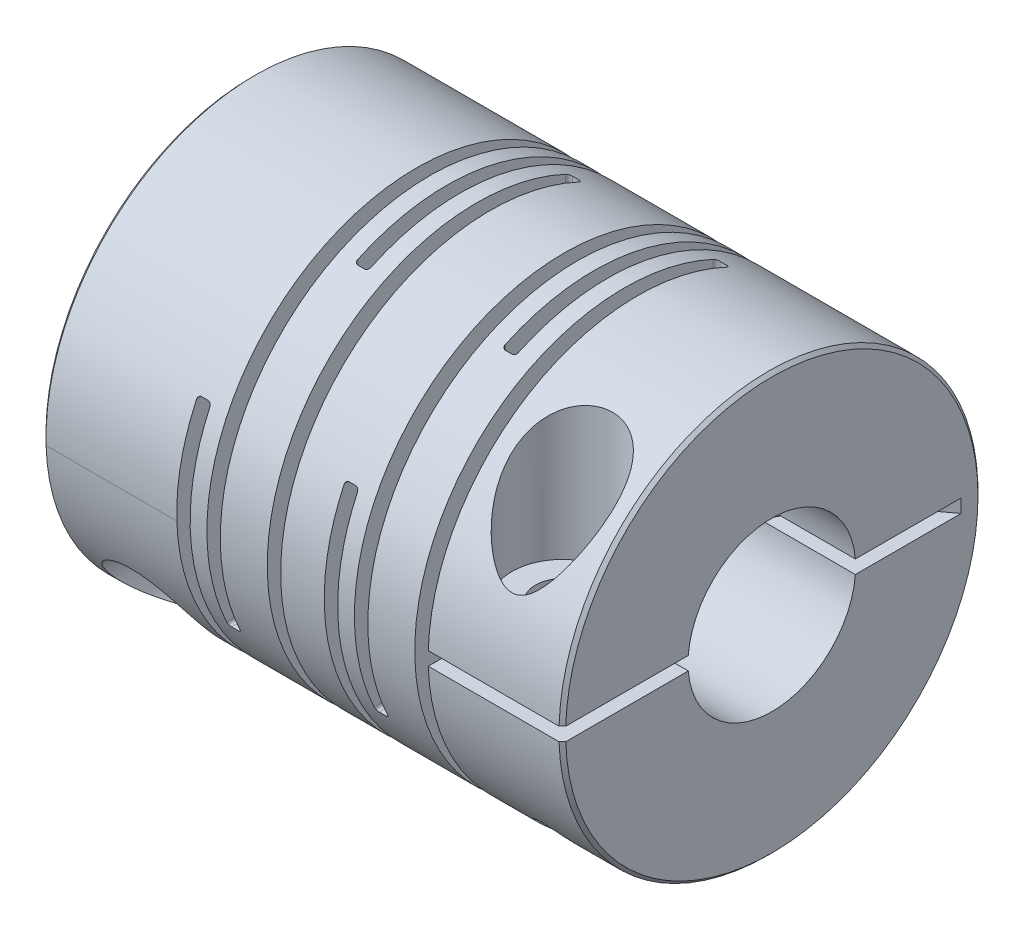
SolidWorks part; units mm, degrees
ref_plane "Front Plane" through (0, 0, 0) normal (0, 0, 1) x (1, 0, 0)
ref_plane "Top Plane" through (0, 0, 0) normal (0, 1, 0) x (1, 0, 0)
ref_plane "Right Plane" through (0, 0, 0) normal (1, 0, 0) x (0, 0, -1)
ref_plane "Plane1" through (0, 0, 12.5) normal (0, 0, 1) x (1, 0, 0)
ref_plane "Plane2" through (0, 12.5, 0) normal (0, 1, 0) x (1, 0, 0)
ref_plane "Plane3" through (31, 0, 0) normal (1, 0, 0) x (0, 0, -1)
sketch "Sketch1" plane through (0, 0, 0) normal (0, 0, 1) x (1, 0, 0)
  line L0 (0, 0) -> (31, 0) construction
  line L1 (0, 0) -> (31, 0)
  line L3 (0, 0) -> (0, 12.5)
  line L4 (0, 12.5) -> (31, 12.5)
  line L5 (31, 0) -> (31, 12.5)
  dimension "L" = 31
  dimension "D" = 25
revolve "Revolve1" add sketch "Sketch1" about L0
sketch "Sketch2" plane through (0, 0, 12.5) normal (0, 0, 1) x (1, 0, 0)
  line L0 (19.4, 12.5) -> (19.4, -5.3)
  line L1 (18.6, -5.3) -> (18.6, 12.5)
  line L2 (18.8, -5.5) -> (19.2, -5.5)
  line L3 (17.6, 5.3) -> (17.6, -12.5)
  line L4 (17.4, 5.5) -> (17, 5.5)
  line L5 (16.8, -12.5) -> (16.8, 5.3)
  line L6 (10.6, 12.5) -> (10.6, -5.3)
  line L7 (10, -5.5) -> (10.4, -5.5)
  line L8 (9.8, -5.3) -> (9.8, 12.5)
  line L9 (8.8, 5.3) -> (8.8, -12.5)
  line L10 (8.6, 5.5) -> (8.2, 5.5)
  line L11 (8, -12.5) -> (8, 5.3)
  line L12 (9.8, 12.5) -> (10.6, 12.5)
  line L13 (8, -12.5) -> (8.8, -12.5)
  line L14 (16.8, -12.5) -> (17.6, -12.5)
  line L15 (18.6, 12.5) -> (19.4, 12.5)
  line L16 (0, 0) -> (31, 0) construction
  line L17 (31, -8.8) -> (31, 8.8) construction
  arc A0 (19.2, -5.5) -> (19.4, -5.3) centre (19.2, -5.3) ccw
  arc A1 (18.6, -5.3) -> (18.8, -5.5) centre (18.8, -5.3) ccw
  arc A2 (17.6, 5.3) -> (17.4, 5.5) centre (17.4, 5.3) ccw
  arc A3 (17, 5.5) -> (16.8, 5.3) centre (17, 5.3) ccw
  arc A4 (10.4, -5.5) -> (10.6, -5.3) centre (10.4, -5.3) ccw
  arc A5 (9.8, -5.3) -> (10, -5.5) centre (10, -5.3) ccw
  arc A6 (8.8, 5.3) -> (8.6, 5.5) centre (8.6, 5.3) ccw
  arc A7 (8.2, 5.5) -> (8, 5.3) centre (8.2, 5.3) ccw
  dimension "FIX_3" = 0.2
  dimension "FIX_1" = 12.5
  dimension "D" = 25
  dimension "L_s" = 8
  dimension "MSM_1" = 5.3
  dimension "MSM_2" = 11.6
  dimension "MSM_4" = 0.8
extrude "Cut-Extrude1" cut sketch "Sketch2" against normal through all
sketch "Sketch3" plane through (0, 12.5, 0) normal (0, 1, 0) x (1, 0, 0)
  line L0 (21.2, 12.5) -> (21.2, -5.3)
  line L1 (20.4, -5.3) -> (20.4, 12.5)
  line L2 (20.6, -5.5) -> (21, -5.5)
  line L3 (23, 5.3) -> (23, -12.5)
  line L4 (22.8, 5.5) -> (22.4, 5.5)
  line L5 (22.2, -12.5) -> (22.2, 5.3)
  line L6 (12.4, 12.5) -> (12.4, -5.3)
  line L7 (11.8, -5.5) -> (12.2, -5.5)
  line L8 (11.6, -5.3) -> (11.6, 12.5)
  line L9 (14.2, 5.3) -> (14.2, -12.5)
  line L10 (14, 5.5) -> (13.6, 5.5)
  line L11 (13.4, -12.5) -> (13.4, 5.3)
  line L12 (11.6, 12.5) -> (12.4, 12.5)
  line L13 (13.4, -12.5) -> (14.2, -12.5)
  line L14 (22.2, -12.5) -> (23, -12.5)
  line L15 (20.4, 12.5) -> (21.2, 12.5)
  line L16 (0, 0) -> (31, 0) construction
  line L17 (31, -8.8) -> (31, 8.8) construction
  arc A0 (21, -5.5) -> (21.2, -5.3) centre (21, -5.3) ccw
  arc A1 (20.4, -5.3) -> (20.6, -5.5) centre (20.6, -5.3) ccw
  arc A2 (23, 5.3) -> (22.8, 5.5) centre (22.8, 5.3) ccw
  arc A3 (22.4, 5.5) -> (22.2, 5.3) centre (22.4, 5.3) ccw
  arc A4 (12.2, -5.5) -> (12.4, -5.3) centre (12.2, -5.3) ccw
  arc A5 (11.6, -5.3) -> (11.8, -5.5) centre (11.8, -5.3) ccw
  arc A6 (14.2, 5.3) -> (14, 5.5) centre (14, 5.3) ccw
  arc A7 (13.6, 5.5) -> (13.4, 5.3) centre (13.6, 5.3) ccw
  dimension "FIX_4" = 0.2
  dimension "FIX_1" = 12.5
  dimension "D" = 25
  dimension "L_s" = 8
  dimension "MSM_1" = 5.3
  dimension "MSM_2" = 11.6
  dimension "MSM_4" = 0.8
extrude "Cut-Extrude2" cut sketch "Sketch3" against normal through all
chamfer "Chamfer1" distance 0.2 2 edges at (31, 0, 12.5) (0, 0, 12.5)
sketch "Sketch4" plane through (0, 0, 0) normal (0, 0, 1) x (1, 0, 0)
  line L1 (0, 0) -> (25.1364, 0) construction
  line L2 (8.4, -12.5) -> (-11.6, -12.5)
  line L3 (-11.6, -12.5) -> (-11.6, 15)
  line L4 (8.4, -5) -> (8.4, -12.5)
  line L6 (-11.6, 15) -> (8.4, 15) construction
  line L7 (8.4, 15) -> (8.4, -12.5) construction
  arc A1 (8.4, -5) -> (-11.6, 15) centre (-11.6, -5) ccw
  dimension "FIX_1" = 12.5
  dimension "MSM_5" = 20
  dimension "MSM_6" = 8.4
  dimension "MSM_7" = 7.5
extrude "Cut-Extrude3" cut sketch "Sketch4" against normal mid plane 0.8
sketch "Sketch5" plane through (0, 0, 0) normal (0, 1, 0) x (1, 0, 0)
  line L0 (22.6, -12.5) -> (42.6, -12.5)
  line L1 (42.6, -12.5) -> (42.6, 15)
  line L2 (22.6, -5) -> (22.6, -12.5)
  line L3 (42.6, 15) -> (22.6, 15) construction
  line L4 (22.6, 15) -> (22.6, -12.5) construction
  line L5 (0, 0) -> (31, 0) construction
  line L6 (31, -8.8) -> (31, 8.8) construction
  arc A0 (42.6, 15) -> (22.6, -5) centre (42.6, -5) ccw
  dimension "FIX_1" = 12.5
  dimension "MSM_5" = 20
  dimension "MSM_6" = 8.4
  dimension "MSM_7" = 7.5
extrude "Cut-Extrude4" cut sketch "Sketch5" against normal mid plane 0.8
hole_wizard "Socket Head Cap Screw1" positions "Sketch8" profile "Sketch7" counterbore size "M2.5" standard "JIS"
sketch "Sketch8" plane through (0, 0, 12.5) normal (0, 0, 1) x (1, 0, 0)
  point P0 (4, -8.5)
  dimension "A" = 8.5
  dimension "F" = 4
sketch "Sketch7" plane through (4, -8.5, 12.5) normal (1, 0, 0) x (0, -1, 0)
  line L0 (0, 0) -> (0, 12.1)
  line L1 (0, 12.1) -> (1.6, 12.1)
  line L3 (1.6, 12.1) -> (1.6, 9.5)
  line L4 (1.6, 9.5) -> (3, 9.5)
  line L5 (3, 9.5) -> (3, 0)
  line L7 (3, 0) -> (0, 0)
  line L11 (0, 0) -> (0, 12.1) construction
  dimension "Thru Hole Depth" = 12.1
  dimension "MSM_8" = 6
  dimension "MSM_9" = 3.2
  dimension "MSM_10" = 9.5
hole_wizard "Tap1" positions "Sketch10" profile "Sketch9" hole size "M2x0.4" standard "JIS" end condition through all
sketch "Sketch10" plane through (0, 0, -0.4) normal (0, 0, 1) x (1, 0, 0)
  point P0 (4, -8.5)
  dimension "A" = 8.5
  dimension "F" = 4
sketch "Sketch9" plane through (4, -8.5, -0.4) normal (1, 0, 0) x (0, -1, 0)
  line L0 (0, 0) -> (0, 12.1)
  line L1 (0, 12.1) -> (1.2295, 12.1)
  line L2 (1.2295, 12.1) -> (1.2295, 0)
  line L5 (1.2295, 0) -> (0, 0)
  line L11 (0, 0) -> (0, 12.1) construction
  dimension "Thru Hole Depth" = 12.1
  dimension "STD" = 2.459
cosmetic thread "Thread1" parameters "M"=3
hole_wizard "Socket Head Cap Screw2" positions "Sketch12" profile "Sketch11" counterbore size "M2.5" standard "JIS"
sketch "Sketch12" plane through (0, 12.5, 0) normal (0, 1, 0) x (1, 0, 0)
  line L4 (31, -8.8) -> (31, 8.8) construction
  point P0 (27, -8.5)
  dimension "A" = 8.5
  dimension "F" = 4
sketch "Sketch11" plane through (27, 12.5, 8.5) normal (1, 0, 0) x (0, 0, 1)
  line L0 (0, 0) -> (0, 12.1)
  line L1 (0, 12.1) -> (1.6, 12.1)
  line L3 (1.6, 12.1) -> (1.6, 9.5)
  line L4 (1.6, 9.5) -> (3, 9.5)
  line L5 (3, 9.5) -> (3, 0)
  line L7 (3, 0) -> (0, 0)
  line L11 (0, 0) -> (0, 12.1) construction
  dimension "Thru Hole Depth" = 12.1
  dimension "MSM_8" = 6
  dimension "MSM_9" = 3.2
  dimension "MSM_10" = 9.5
hole_wizard "Tap2" positions "Sketch14" profile "Sketch13" hole size "M2x0.4" standard "JIS" end condition through all
sketch "Sketch14" plane through (0, -0.4, 0) normal (0, 1, 0) x (1, 0, 0)
  line L0 (31, -8.8) -> (31, 8.8) construction
  point P0 (27, -8.5)
  dimension "A" = 8.5
  dimension "F" = 4
sketch "Sketch13" plane through (27, -0.4, 8.5) normal (1, 0, 0) x (0, 0, 1)
  line L0 (0, 0) -> (0, 12.1)
  line L1 (0, 12.1) -> (1.2295, 12.1)
  line L2 (1.2295, 12.1) -> (1.2295, 0)
  line L5 (1.2295, 0) -> (0, 0)
  line L11 (0, 0) -> (0, 12.1) construction
  dimension "Thru Hole Depth" = 12.1
  dimension "STD" = 2.459
cosmetic thread "Thread2" parameters "M"=3
sketch "Sketch15" plane through (0, 0, 0) normal (0, 0, 1) x (1, 0, 0)
  line L0 (0, 0) -> (31, 0) construction
  line L1 (31, -8.8) -> (31, 8.8) construction
  line L2 (8, -12.5) -> (8, 5.3) construction
  line L3 (0, 0) -> (31, 0) construction
  line L4 (8, 0) -> (8, 4.25)
  line L5 (8, 4.25) -> (23, 4.25)
  line L6 (23, 0) -> (23, 4.25)
  line L7 (8, 0) -> (23, 0)
  dimension "FIX_9" = 8.5
revolve "Cut-Revolve1" [suppressed] cut sketch "Sketch15" about L0
sketch "Sketch16" plane through (0, 0, 0) normal (0, 0, 1) x (1, 0, 0)
  line L0 (0, 0.0033) -> (31, 0.0033) construction
  line L1 (0, 12.3) -> (0, -12.2935) construction
  line L2 (31, -8.8) -> (31, 8.8) construction
  line L3 (8, 0.0033) -> (8, 5.0033)
  line L4 (8, 5.0033) -> (23, 5.0033)
  line L5 (23, 5.0033) -> (23, 0.0033)
  line L6 (8, -12.5) -> (8, 5.3) construction
  line L7 (8, 0.0033) -> (23, 0.0033)
  dimension "D2_s" = 10
revolve "Cut-Revolve2" cut sketch "Sketch16" about L0
sketch "Sketch17" plane through (0, 0, 0) normal (1, 0, 0) x (0, 0, -1)
  circle A0 centre (0, 0) radius 4
  dimension "D1_s" = 8
extrude "Cut-Extrude5" cut sketch "Sketch17" along normal up to surface (8 mm away)
sketch "Sketch18" plane through (31, 0, 0) normal (1, 0, 0) x (0, 0, -1)
  circle A0 centre (0, 0) radius 5
  dimension "D2_s" = 10
extrude "Cut-Extrude6" cut sketch "Sketch18" against normal up to surface (8 mm away)
equation "\"FIX_1@Plane1\"= \"D@Sketch1\" / 2"
equation "\"FIX_9@Sketch15\"= \"D1_s@Sketch17\" + 0.5"
equation "\"Cut-Revolve1\" = if ( \"D1_s@Sketch17\" = \"D2_s@Sketch18\" , \"unsuppressed\" , \"suppressed\" )"
equation "\"Cut-Revolve2\" = if ( \"D1_s@Sketch17\" < > \"D2_s@Sketch18\" , \"unsuppressed\" , \"suppressed\" )"
